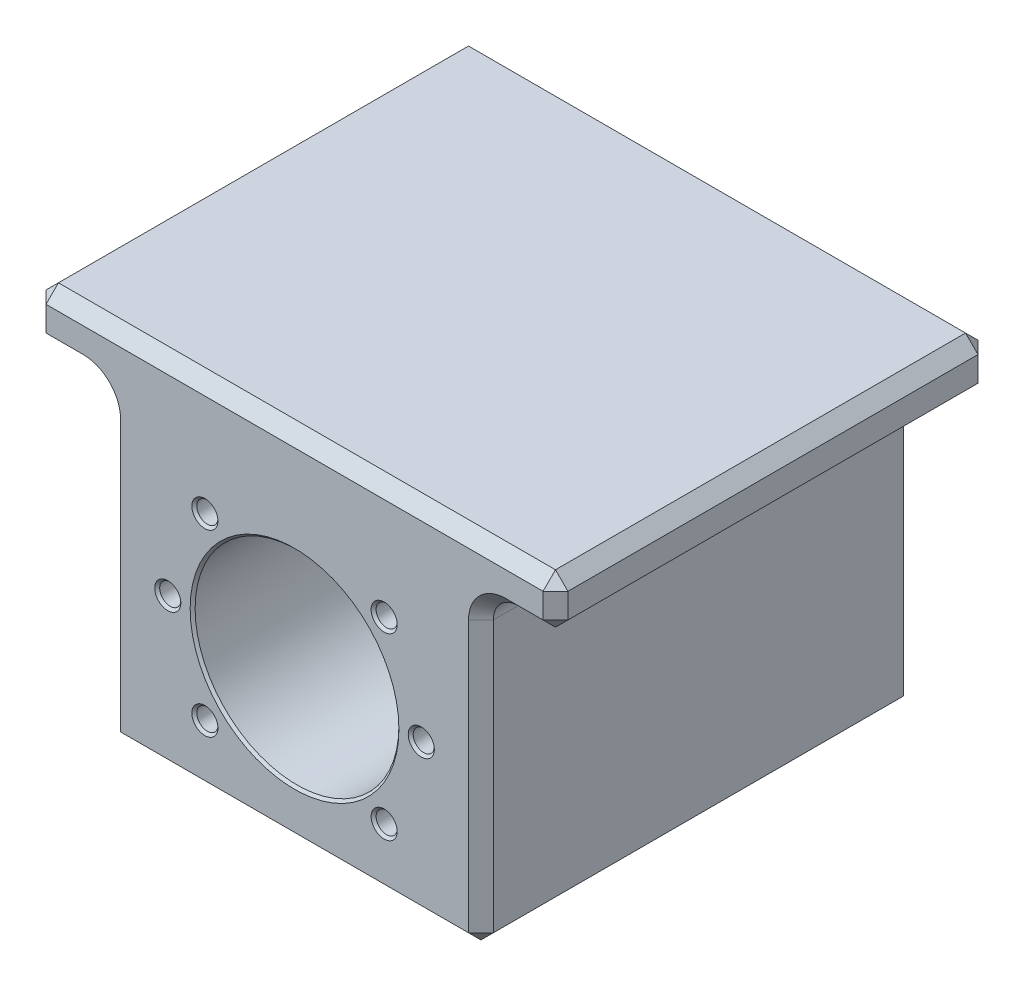
SolidWorks part; units mm, degrees
material "Plain Carbon Steel"
ref_plane "Front Plane" through (0, 0, 0) normal (0, 0, 1) x (1, 0, 0)
ref_plane "Top Plane" through (0, 0, 0) normal (0, 1, 0) x (1, 0, 0)
ref_plane "Right Plane" through (0, 0, 0) normal (1, 0, 0) x (0, 0, -1)
sketch "Sketch1" plane through (0, 0, 0) normal (0, 0, 1) x (1, 0, 0)
  line L1 (-75, -62) -> (75, -62)
  line L2 (-75, -62) -> (-75, 62)
  line L3 (-75, 62) -> (75, 62)
  line L4 (75, -62) -> (75, 62)
  line L5 (-75, -62) -> (75, 62) construction
  line L6 (-75, 62) -> (75, -62) construction
  point P0 (0, 0)
  dimension "D1" = 150
  dimension "D2" = 124
extrude "Boss-Extrude1" add sketch "Sketch1" along normal mid plane 175
sketch "Sketch8" plane through (0, 0, 0) normal (0, 0, 1) x (1, 0, 0)
  line L0 (0, 0) -> (0, 82) construction
  line L1 (-105, 62) -> (105, 62)
  line L2 (-105, 62) -> (-105, 82)
  line L3 (-105, 82) -> (105, 82)
  line L4 (105, 62) -> (105, 82)
  line L6 (75, 62) -> (-75, 62) construction
  dimension "D1" = 20
  dimension "D2" = 210
extrude "Boss-Extrude2" add sketch "Sketch8" against normal up to surface and the other way up to surface up to face at (0, 0, -87.5) other way up to face at (0, 0, 87.5)
sketch "Sketch2" plane through (0, 0, 87.5) normal (0, 0, 1) x (1, 0, 0)
  circle A0 centre (0, 0) radius 41
  dimension "D1" = 82
extrude "Cut-Extrude1" cut sketch "Sketch2" against normal up to next
hole_wizard "M10 Tapped Hole1" positions "Sketch6" profile "Sketch4" tap size "M10" standard "ISO"
sketch "Sketch6" plane through (0, 0, 87.5) normal (0, 0, 1) x (1, 0, 0)
  line L0 (0, 0) -> (-36.0624, 36.0624) construction
  line L2 (0, 0) -> (-36.0624, -36.0624) construction
  line L4 (0, 0) -> (-51, 0) construction
  line L5 (0, 51) -> (0, -51) construction
  circle A0 centre (0, 0) radius 51 construction
  point P7 (-36.0624, 36.0624)
  point P12 (-36.0624, -36.0624)
  point P16 (-51, 0)
  point P32 (36.0624, 36.0624)
  point P33 (51, 0)
  point P34 (36.0624, -36.0624)
  point P35 (-36.0624, 36.0624)
  point P37 (-51, 0)
  point P39 (-36.0624, -36.0624)
  dimension "D1" = 102
  dimension "D2" = 45
  dimension "D3" = 45
sketch "Sketch4" plane through (-36.0624, -36.0624, 87.5) normal (1, 0, 0) x (0, -1, 0)
  line L0 (0, 0) -> (0, 30.0537)
  line L1 (0, 30.0537) -> (4.25, 27.5)
  line L2 (4.25, 27.5) -> (4.25, 0)
  line L5 (4.25, 0) -> (0, 0)
  line L10 (0, 30.0537) -> (-4.25, 27.5) construction
  line L11 (0, -6.35) -> (0, 107.95) construction
  dimension "Tap Drill Dia." = 8.5
  dimension "Tap Drill Depth" = 27.5
  dimension "Drill Angle" = 118
cosmetic thread "Hole Thread1" parameters "D1"=20, "D2"=10
cosmetic thread "Hole Thread2" parameters "D1"=20, "D2"=10
cosmetic thread "Hole Thread3" parameters "D1"=20, "D2"=10
cosmetic thread "Hole Thread4" parameters "D1"=20, "D2"=10
cosmetic thread "Hole Thread5" parameters "D1"=20, "D2"=10
cosmetic thread "Hole Thread6" parameters "D1"=20, "D2"=10
fillet "Fillet1" radius 10 2 edges at (-75, 62, 0) (75, 62, 0)
chamfer "Chamfer1" distance 5 angle 45 26 edges at (-75, -62, 0) (75, -62, 0) (0, -62, 87.5) (-75, -5, 87.5) (75, -5, 87.5) (-75, -5, -87.5) (0, -62, -87.5) (75, -5, -87.5) (-95, 62, -87.5) (-95, 62, 87.5) (-105, 72, -87.5) (-105, 72, 87.5) (0, 82, -87.5) (0, 82, 87.5) (105, 72, -87.5) (105, 72, 87.5) (95, 62, 87.5) (95, 62, -87.5) (-105, 62, 0) (-105, 82, 0) (105, 82, 0) (105, 62, 0) (-77.9289, 59.0711, 87.5) (77.9289, 59.0711, 87.5) (77.9289, 59.0711, -87.5) (-77.9289, 59.0711, -87.5)
chamfer "Chamfer2" distance 1 angle 45 8 edges at (41, 0, 87.5) (-41, 0, -87.5) (-46.75, 0, 87.5) (-31.8124, 36.0624, 87.5) (40.3124, 36.0624, 87.5) (55.25, 0, 87.5) (40.3124, -36.0624, 87.5) (-31.8124, -36.0624, 87.5)
